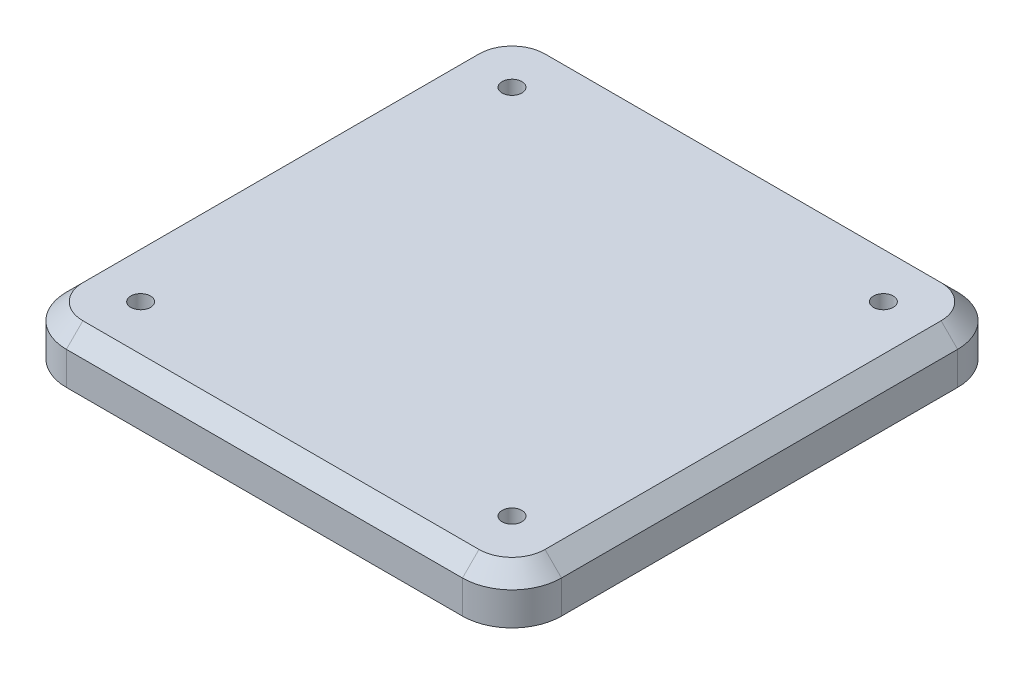
SolidWorks part; units mm, degrees
ref_plane "前基準面" through (0, 0, 0) normal (0, 0, 1) x (1, 0, 0)
ref_plane "上基準面" through (0, 0, 0) normal (0, 1, 0) x (1, 0, 0)
ref_plane "右基準面" through (0, 0, 0) normal (1, 0, 0) x (0, 0, -1)
sketch "草圖1" plane through (0, 0, 0) normal (0, 1, 0) x (1, 0, 0)
  line L1 (0, 0) -> (300, 0)
  line L2 (0, 0) -> (0, 300)
  line L3 (0, 300) -> (300, 300)
  line L4 (300, 0) -> (300, 300)
  dimension "D1" = 300
  dimension "D2" = 300
extrude "填料-伸長1" add sketch "草圖1" along normal blind 30
fillet "圓角1" radius 30 4 edges at (0, 15, -300) (300, 15, -300) (300, 15, 0) (0, 15, 0)
chamfer "導角1" distance 10 angle 45 8 edges at (0, 30, -150) (8.7868, 30, -8.7868) (8.7868, 30, -291.2132) (150, 30, 0) (150, 30, -300) (291.2132, 30, -8.7868) (291.2132, 30, -291.2132) (300, 30, -150)
sketch "草圖2" plane through (0, 0, 0) normal (0, -1, 0) x (1, 0, 0)
  line L0 (30, 0) -> (270, 0) construction
  line L1 (25, -25) -> (275, -25)
  line L2 (25, -25) -> (25, -275)
  line L3 (25, -275) -> (275, -275)
  line L4 (275, -25) -> (275, -275)
  line L5 (270, -300) -> (30, -300) construction
  line L6 (300, -30) -> (300, -270) construction
  line L7 (0, -270) -> (0, -30) construction
  dimension "D1" = 25
  dimension "D2" = 25
  dimension "D3" = 25
  dimension "D4" = 25
sketch "草圖4" plane through (0, 30, 0) normal (0, 1, 0) x (1, 0, 0)
  line L0 (25, 25) -> (25, 275) construction
  line L1 (37.5, 37.5) -> (262.5, 37.5)
  line L2 (37.5, 37.5) -> (37.5, 262.5)
  line L3 (37.5, 262.5) -> (262.5, 262.5)
  line L4 (262.5, 37.5) -> (262.5, 262.5)
  line L5 (25, 25) -> (275, 25) construction
  line L6 (275, 25) -> (275, 275) construction
  line L7 (25, 275) -> (275, 275) construction
  dimension "D1" = 12.5
  dimension "D2" = 12.5
  dimension "D3" = 12.5
  dimension "D4" = 12.5
hole_wizard "Ø20.0mm 定位孔1" positions "3D草圖2" profile "草圖6" hole size "Ø20.0" standard "ISO"
sketch3d "3D草圖2"
  point P0 (37.5, 30, -37.5)
  point P3 (37.5, 30, -262.5)
  point P6 (262.5, 30, -262.5)
  point P9 (262.5, 30, -37.5)
  point P12 (25, 0, -25)
  point P15 (275, 0, -25)
  point P18 (275, 0, -275)
  point P25 (25, 0, -275)
  point P29 (0, 0, 0)
sketch "草圖6" plane through (37.5, 30, -37.5) normal (1, 0, 0) x (0, 0, 1)
  line L0 (0, 0) -> (0, 13.6052)
  line L1 (0, 13.6052) -> (6, 10)
  line L2 (6, 10) -> (6, 0)
  line L5 (6, 0) -> (0, 0)
  line L10 (0, 13.6052) -> (-6, 10) construction
  line L11 (0, -6.35) -> (0, 107.95) construction
  dimension "鑽孔直徑" = 12
  dimension "鑽孔深度" = 10
  dimension "導頭角度" = 118
